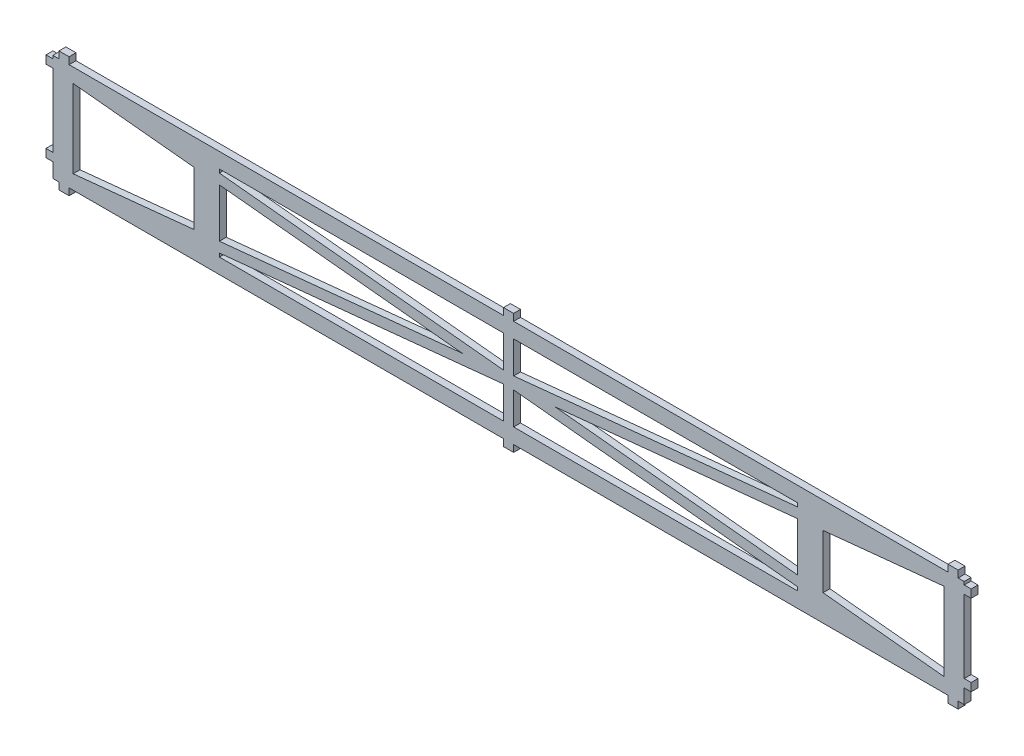
SolidWorks part; units mm, degrees
material "Delrin 2700 NC010, Low Viscosity Acetal Copolymer (SS)"
ref_plane "Front Plane" through (0, 0, 0) normal (0, 0, 1) x (1, 0, 0)
ref_plane "Top Plane" through (0, 0, 0) normal (0, 1, 0) x (1, 0, 0)
ref_plane "Right Plane" through (0, 0, 0) normal (1, 0, 0) x (0, 0, -1)
sketch "Sketch1" plane through (0, 0, 0) normal (0, 0, 1) x (1, 0, 0)
  line L0 (0, 13.3795) -> (0, -13.3795) construction
  line L1 (-114.3, 13.3795) -> (-112.776, 13.3795)
  line L2 (-114.3, 13.3795) -> (-114.3, 12.6175)
  line L3 (-114.3, -13.3795) -> (-112.776, -13.3795)
  line L4 (114.3, -13.3794) -> (112.776, -13.3794)
  line L5 (-114.3, 0) -> (123.7225, 0) construction
  line L6 (-1.27, -1.5173) -> (-72.54, -8.6776)
  line L7 (-72.54, -8.6776) -> (-72.54, -9.5694)
  line L8 (-78.89, -6.7628) -> (-109.22, -9.8099)
  line L9 (-109.22, -9.8099) -> (-109.22, 9.8099)
  line L10 (-81.4172, 9.5694) -> (-78.89, 9.5694) construction
  line L11 (-78.89, -6.7628) -> (-78.89, 6.7628)
  line L12 (-78.89, -9.3155) -> (-81.4172, -9.5694) construction
  line L13 (-1.27, -9.5694) -> (-1.27, -1.5173)
  line L14 (-11.5765, 0) -> (-72.54, -6.1248)
  line L15 (-78.89, -9.3155) -> (-78.89, -9.5694) construction
  line L16 (-1.27, 9.5694) -> (-72.54, 9.5694)
  line L17 (-1.27, -9.5694) -> (-72.54, -9.5694)
  line L18 (-81.4172, -9.5694) -> (-78.89, -9.5694) construction
  line L19 (1.27, 1.5173) -> (72.54, 8.6776)
  line L20 (72.54, 8.6776) -> (72.54, 9.5694)
  line L21 (-78.89, 9.3155) -> (-78.89, 9.5694) construction
  line L22 (78.89, 6.7628) -> (109.22, 9.8099)
  line L23 (78.89, 9.3155) -> (81.4172, 9.5694) construction
  line L24 (1.27, 9.5694) -> (1.27, 1.5173)
  line L25 (-11.5765, 0) -> (-72.54, 6.1248)
  line L26 (72.54, -6.1248) -> (72.54, 6.1248)
  line L27 (-72.54, -6.1248) -> (-72.54, 6.1248)
  line L28 (11.5765, 0) -> (72.54, 6.1248)
  line L29 (78.89, 9.3155) -> (78.89, 9.5694) construction
  line L30 (81.4172, -9.5694) -> (78.89, -9.5694) construction
  line L31 (1.27, -9.5694) -> (72.54, -9.5694)
  line L32 (1.27, 9.5694) -> (72.54, 9.5694)
  line L33 (78.89, -9.3155) -> (78.89, -9.5694) construction
  line L34 (-1.27, 9.5694) -> (-1.27, 1.5173)
  line L35 (11.5765, 0) -> (72.54, -6.1248)
  line L36 (1.27, -9.5694) -> (1.27, -1.5173)
  line L37 (78.89, -9.3155) -> (81.4172, -9.5694) construction
  line L38 (78.89, -6.7628) -> (78.89, 6.7628)
  line L39 (-1.27, 13.3795) -> (-1.27, -13.3795) construction
  line L40 (-78.89, 9.3155) -> (-81.4172, 9.5694) construction
  line L41 (-78.89, 6.7628) -> (-109.22, 9.8099)
  line L42 (81.4172, 9.5694) -> (78.89, 9.5694) construction
  line L43 (-72.54, 8.6776) -> (-72.54, 9.5694)
  line L44 (109.22, -9.8099) -> (109.22, 9.8099)
  line L45 (-1.27, 1.5173) -> (-72.54, 8.6776)
  line L46 (78.89, -6.7628) -> (109.22, -9.8099)
  line L47 (72.54, -8.6776) -> (72.54, -9.5694)
  line L48 (1.27, -1.5173) -> (72.54, -8.6776)
  line L49 (-110.236, 13.3795) -> (-1.27, 13.3795)
  line L50 (-110.236, -13.3795) -> (-110.236, -15.1067)
  line L51 (-112.776, 13.3795) -> (-112.776, 15.1067)
  line L52 (-112.776, 15.1067) -> (-110.236, 15.1067)
  line L53 (-110.236, 13.3795) -> (-110.236, 15.1067)
  line L54 (-112.776, -15.1067) -> (-110.236, -15.1067)
  line L55 (-112.776, -13.3795) -> (-112.776, -15.1067)
  line L56 (112.776, -13.3794) -> (112.776, -15.1066)
  line L57 (112.776, -15.1066) -> (110.236, -15.1066)
  line L58 (110.236, -13.3795) -> (110.236, -15.1066)
  line L59 (110.236, 13.3795) -> (110.236, 15.1066)
  line L60 (112.776, 15.1066) -> (110.236, 15.1066)
  line L61 (112.776, 13.3794) -> (112.776, 15.1066)
  line L62 (-110.236, -13.3795) -> (-1.27, -13.3795)
  line L63 (114.3, 13.3795) -> (112.776, 13.3794)
  line L64 (114.3, 13.3795) -> (114.3, 12.6175)
  line L65 (1.27, 13.3795) -> (110.236, 13.3795)
  line L66 (-1.27, -13.3795) -> (-1.27, -15.1067)
  line L67 (-1.27, 13.3795) -> (-1.27, 15.1067)
  line L68 (-1.27, 15.1067) -> (1.27, 15.1067)
  line L69 (1.27, 13.3795) -> (1.27, 15.1067)
  line L70 (1.27, -13.3795) -> (1.27, -15.1067)
  line L71 (-1.27, -15.1067) -> (1.27, -15.1067)
  line L72 (1.27, -13.3795) -> (110.236, -13.3795)
  line L73 (-114.3, 10.5855) -> (-114.3, -7.7025)
  line L74 (-114.3, 12.6175) -> (-116.0272, 12.6175)
  line L75 (-114.3, -7.7025) -> (-116.0272, -7.7025)
  line L76 (-114.3, 10.5855) -> (-116.0272, 10.5855)
  line L77 (-116.0272, 12.6175) -> (-116.0272, 10.5855)
  line L78 (-114.3, -9.7345) -> (-116.0272, -9.7345)
  line L79 (-116.0272, -7.7025) -> (-116.0272, -9.7345)
  line L80 (-114.3, -9.7345) -> (-114.3, -13.3795)
  line L81 (116.0272, -7.7025) -> (116.0272, -9.7345)
  line L82 (114.3, -9.7345) -> (116.0272, -9.7345)
  line L83 (116.0272, 12.6175) -> (116.0272, 10.5855)
  line L84 (114.3, 10.5855) -> (116.0272, 10.5855)
  line L85 (114.3, -7.7025) -> (116.0272, -7.7025)
  line L86 (114.3, 12.6175) -> (116.0272, 12.6175)
  line L87 (114.3, 10.5855) -> (114.3, -7.7025)
  line L88 (114.3, -9.7345) -> (114.3, -13.3794)
  point P9 (-109.22, 0)
  point P12 (-109.22, 0)
  point P26 (-72.54, 0)
  point P27 (-78.89, 0)
  point P40 (-78.89, 0)
  point P52 (78.89, 0)
  point P53 (72.54, 0)
  point P54 (109.22, 0)
  point P101 (0, 15.1067)
  dimension "D4" = 2.54
  dimension "D7" = 114.3
  dimension "D9" = 1.7272
  dimension "D13" = 0.762
  dimension "D1" = 5.08
  dimension "D2" = 13.3795
  dimension "D5" = 6.35
  dimension "D6" = 1.27
  dimension "D8" = 35.41
  dimension "D10" = 2.54
  dimension "D11" = 1.524
  dimension "D12" = 2.54
  dimension "D15" = 1.7272
  dimension "D16" = 2
  dimension "D14" = 2.032
  dimension "D3" = 3.81
extrude "Boss-Extrude1" add sketch "Sketch1" along normal blind 1.7272
